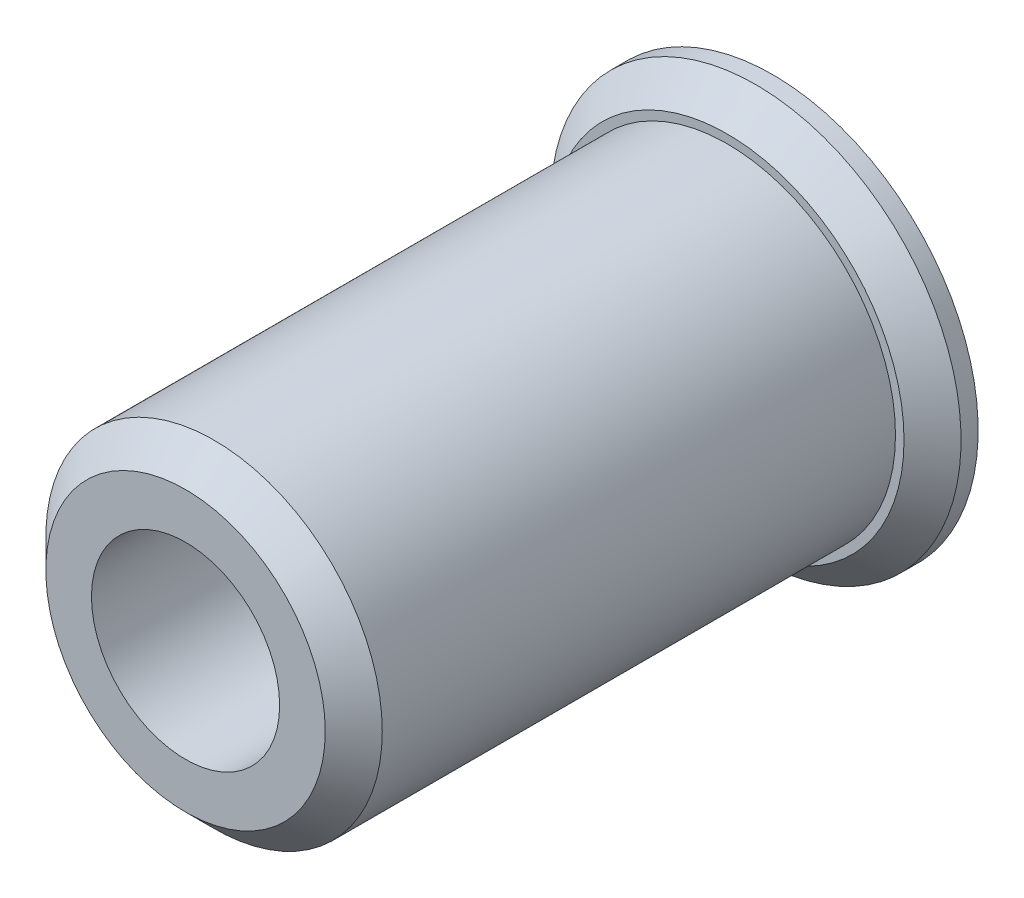
SolidWorks part; units mm, degrees
ref_plane "Plan de face" through (0, 0, 0) normal (0, 0, 1) x (1, 0, 0)
ref_plane "Plan de dessus" through (0, 0, 0) normal (0, 1, 0) x (1, 0, 0)
ref_plane "Plan de droite" through (0, 0, 0) normal (1, 0, 0) x (0, 0, -1)
sketch "Esquisse1" plane through (0, 0, 0) normal (0, 0, 1) x (1, 0, 0)
  circle A0 centre (0, 0) radius 3.6
  dimension "D1" = 7.2
extrude "Boss.-Extru.1" add sketch "Esquisse1" along normal blind 10.3
sketch "Esquisse2" plane through (0, 0, 10.3) normal (0, 0, 1) x (1, 0, 0)
  circle A0 centre (0, 0) radius 2.95
  dimension "D1" = 5.9
extrude "Enlèv. mat.-Extru.1" cut sketch "Esquisse2" against normal blind 9.5 flip side to cut
hole_wizard "Trou taraudé M41" positions "Esquisse4" profile "Esquisse3" tap size "M4" standard "ISO" end condition through all
sketch "Esquisse4" plane through (0, 0, 0) normal (0, 0, -1) x (-1, 0, 0)
  point P0 (0, 0)
sketch "Esquisse3" plane through (0, 0, 0) normal (1, 0, 0) x (0, 1, 0)
  line L0 (0, 0) -> (0, 10.3)
  line L1 (0, 10.3) -> (1.65, 10.3)
  line L2 (1.65, 10.3) -> (1.65, 0)
  line L5 (1.65, 0) -> (0, 0)
  line L11 (0, -6.35) -> (0, 107.95) construction
  dimension "Diamètre du trou pour taraudage jusqu'au prochain" = 3.3
  dimension "Profondeur du trou pour taraudage jusqu'au prochain" = 10.3
cosmetic thread "Filetage de perçage1"
chamfer "Chanfrein1" distance 0.5 angle 45 2 edges at (3.6, 0, 0.8) (2.95, 0, 10.3)
